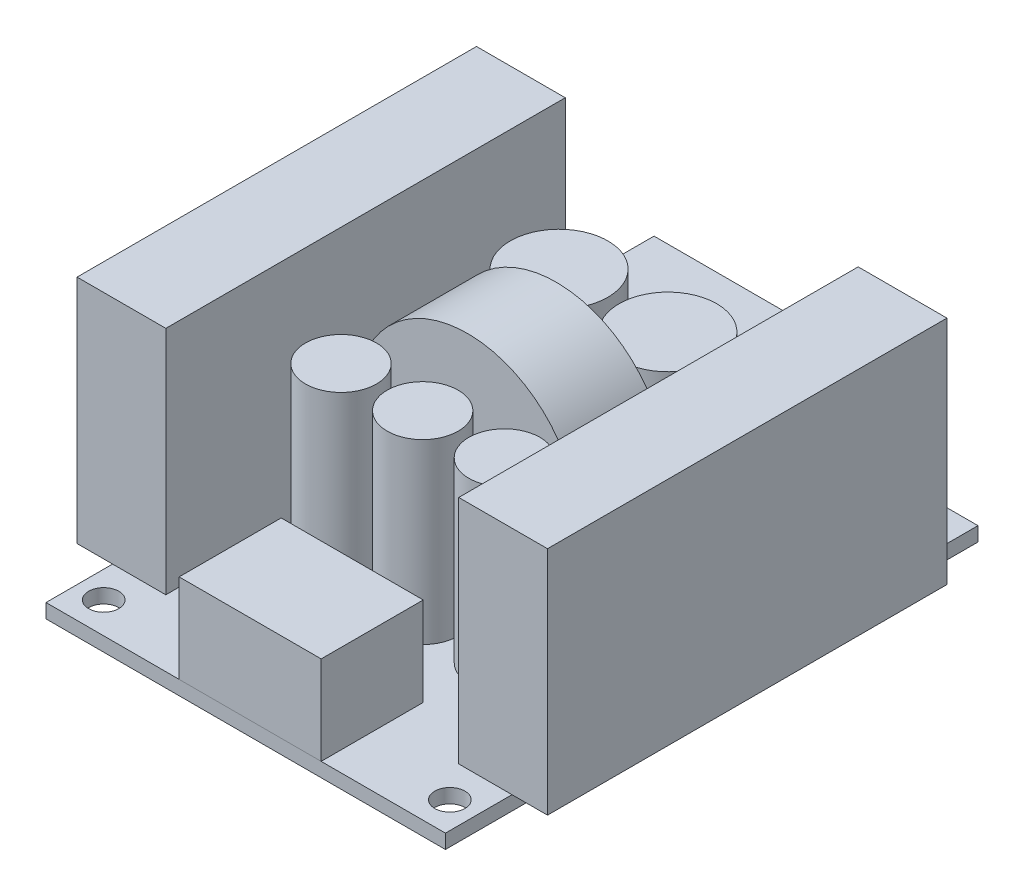
SolidWorks part; units mm, degrees
ref_plane "Plan de face" through (0, 0, 0) normal (0, 0, 1) x (1, 0, 0)
ref_plane "Plan de dessus" through (0, 0, 0) normal (0, 1, 0) x (1, 0, 0)
ref_plane "Plan de droite" through (0, 0, 0) normal (1, 0, 0) x (0, 0, -1)
sketch "Esquisse1" plane through (0, 0, 0) normal (0, 1, 0) x (1, 0, 0)
  line L0 (-22.5, -30) -> (22.5, 30) construction
  line L1 (-22.5, -30) -> (22.5, -30)
  line L2 (-22.5, -30) -> (-22.5, 30)
  line L3 (-22.5, 30) -> (22.5, 30)
  line L4 (22.5, -30) -> (22.5, 30)
  point P5 (0, 0)
  dimension "D1" = 60
  dimension "D2" = 45
extrude "Boss.-Extru.1" add sketch "Esquisse1" along normal blind 1.6
sketch "Esquisse2" plane through (0, 1.6, 0) normal (0, 1, 0) x (1, 0, 0)
  line L0 (0, -30) -> (0, 6.6579) construction
  line L1 (-26.5, 22.5) -> (-16.5, 22.5)
  line L2 (-26.5, 22.5) -> (-26.5, -22.5)
  line L3 (-26.5, -22.5) -> (-16.5, -22.5)
  line L4 (-16.5, 22.5) -> (-16.5, -22.5)
  line L5 (-22.5, -30) -> (22.5, -30) construction
  line L6 (16.5, 22.5) -> (16.5, -22.5)
  line L7 (26.5, -22.5) -> (16.5, -22.5)
  line L8 (26.5, 22.5) -> (26.5, -22.5)
  line L9 (26.5, 22.5) -> (16.5, 22.5)
  line L10 (-22.5, 0) -> (-26.5, 0) construction
  line L11 (-22.5, 30) -> (-22.5, -30) construction
  dimension "D1" = 53
  dimension "D2" = 45
  dimension "D3" = 10
extrude "Boss.-Extru.2" add sketch "Esquisse2" along normal blind 26 separate body
hole_wizard "Dégagement M31" positions "Esquisse4" profile "Esquisse5" hole size "M3" standard "ISO" end condition through all
sketch "Esquisse4" plane through (0, 1.6, 0) normal (0, 1, 0) x (1, 0, 0)
  line L0 (0, -30) -> (0, 3.9551) construction
  line L1 (-22.5, -30) -> (22.5, -30) construction
  line L3 (-22.5, 0) -> (5.6084, 0) construction
  line L8 (-22.5, 30) -> (-22.5, -30) construction
  point P0 (-19.5, 26.5)
  point P15 (-19.5, -26.5)
  point P16 (19.5, 26.5)
  point P17 (19.5, -26.5)
  dimension "D1" = 39
  dimension "D2" = 53
sketch "Esquisse5" plane through (-19.5, 1.6, -26.5) normal (1, 0, 0) x (0, 0, 1)
  line L0 (0, 0) -> (0, 1.6)
  line L1 (0, 1.6) -> (1.7, 1.6)
  line L2 (1.7, 1.6) -> (1.7, 0)
  line L5 (1.7, 0) -> (0, 0)
  line L11 (0, -6.35) -> (0, 107.95) construction
  dimension "Diamètre du perçage jusqu'au prochain" = 3.4
  dimension "Profondeur du perçage jusqu'au prochain" = 1.6
sketch "Esquisse6" plane through (0, 1.6, 0) normal (0, 1, 0) x (1, 0, 0)
  line L0 (-22.5, -30) -> (22.5, -30) construction
  line L1 (8.5, -30) -> (-7.5, -30)
  line L2 (8.5, -30) -> (8.5, -18.5)
  line L3 (8.5, -18.5) -> (-7.5, -18.5)
  line L4 (-7.5, -30) -> (-7.5, -18.5)
  line L5 (22.5, 30) -> (-22.5, 30) construction
  line L6 (-14, 30) -> (2, 30)
  line L7 (-14, 30) -> (-14, 18.5)
  line L8 (-14, 18.5) -> (2, 18.5)
  line L9 (2, 30) -> (2, 18.5)
  line L10 (-22.5, 30) -> (-22.5, -30) construction
  dimension "D1" = 11.5
  dimension "D2" = 16
  dimension "D3" = 15
  dimension "D4" = 8.5
extrude "Boss.-Extru.3" add sketch "Esquisse6" along normal blind 10 separate body
sketch "Esquisse8" plane through (0, 0, 0) normal (0, 0, 1) x (1, 0, 0)
  line L0 (-22.5, 1.6) -> (22.5, 1.6) construction
  circle A0 centre (0, 14.1) radius 12.5
  dimension "D1" = 25
extrude "Boss.-Extru.6" add sketch "Esquisse8" along normal mid plane 10 separate body
sketch "Esquisse7" plane through (0, 1.6, 0) normal (0, 1, 0) x (1, 0, 0)
  line L0 (0, -30) -> (0, 11.8996) construction
  line L1 (-22.5, -30) -> (22.5, -30) construction
  circle A0 centre (-6.1309, 11.4335) radius 5.5
  circle A2 centre (6.1309, 11.4335) radius 5.5
  circle A3 centre (0, -10.0611) radius 4
  circle A4 centre (-9.2049, -10.0611) radius 4
  circle A5 centre (9.2049, -10.0611) radius 4
  dimension "D1" = 11
  dimension "D2" = 8
extrude "Boss.-Extru.4" add sketch "Esquisse7" along normal blind 20 separate body
